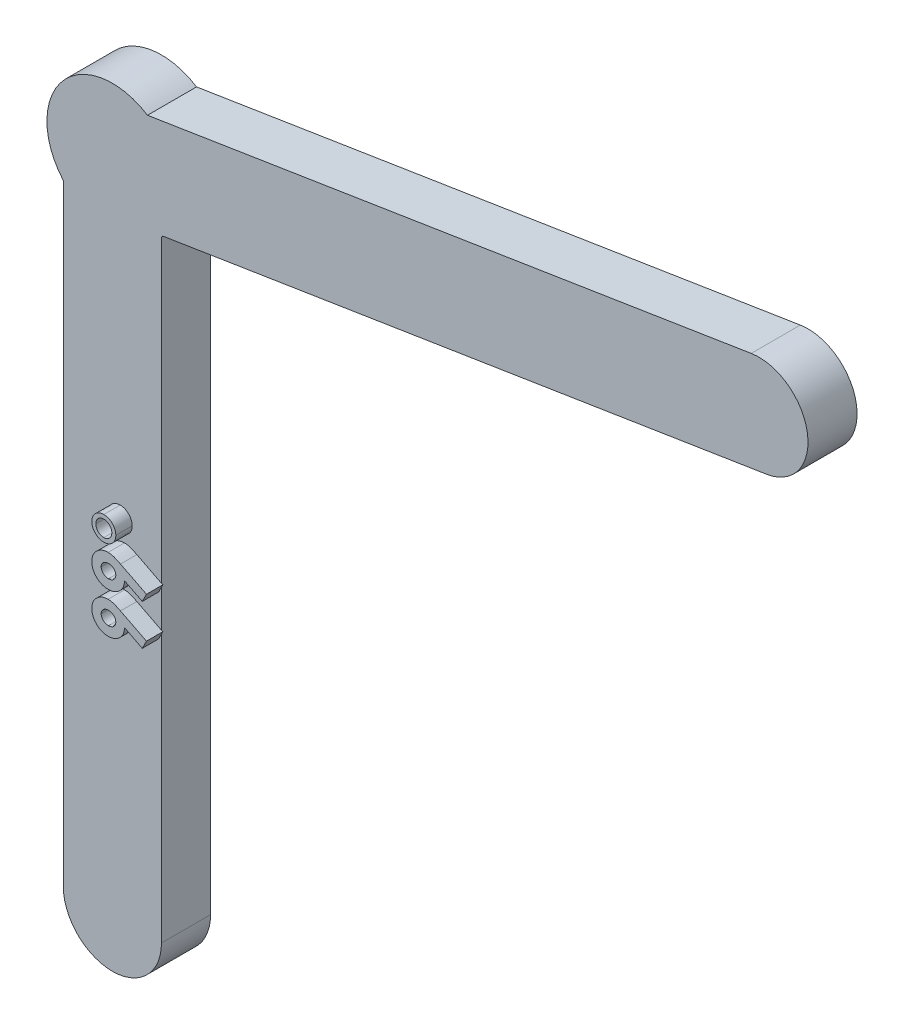
SolidWorks part; units mm, degrees
ref_plane "Front Plane" through (0, 0, 0) normal (0, 0, 1) x (1, 0, 0)
ref_plane "Top Plane" through (0, 0, 0) normal (0, 1, 0) x (1, 0, 0)
ref_plane "Right Plane" through (0, 0, 0) normal (1, 0, 0) x (0, 0, -1)
sketch "Sketch2" plane through (0, 0, 0) normal (0, 0, 1) x (1, 0, 0)
  line L0 (0, 0) -> (0, -40) construction
  line L1 (0, 0) -> (39.5075, 6.2574) construction
  line L2 (39.0382, 9.2204) -> (39.9768, 3.2943) construction
  line L3 (-3, -40) -> (3, -40) construction
  line L4 (-3, -40) -> (-3, -2.6458)
  line L5 (3, -40) -> (3, -2.6458)
  line L6 (39.0382, 9.2204) -> (2.1439, 3.377)
  line L7 (39.9768, 3.2943) -> (3.0825, -2.5492)
  arc A0 (2.1439, 3.377) -> (-3, -2.6458) centre (0, 0) ccw
  arc A1 (-3, -40) -> (3, -40) centre (0, -40) ccw
  arc A2 (39.0382, 9.2204) -> (39.9768, 3.2943) centre (39.5075, 6.2574) cw
  arc A3 (3, -2.6458) -> (3.0825, -2.5492) centre (0, 0) ccw
  point P12 (39.5075, 6.2574)
  dimension "D3" = 3
  dimension "D4" = 8
  dimension "D1" = 40
  dimension "D2" = 99
extrude "Boss-Extrude1" add sketch "Sketch2" along normal blind 3
sketch "Sketch3" plane through (0, 0, 3) normal (0, 0, 1) x (1, 0, 0)
  text T0 "<b>99°</b>"
extrude "Boss-Extrude2" add sketch "Sketch3" along normal blind 1
